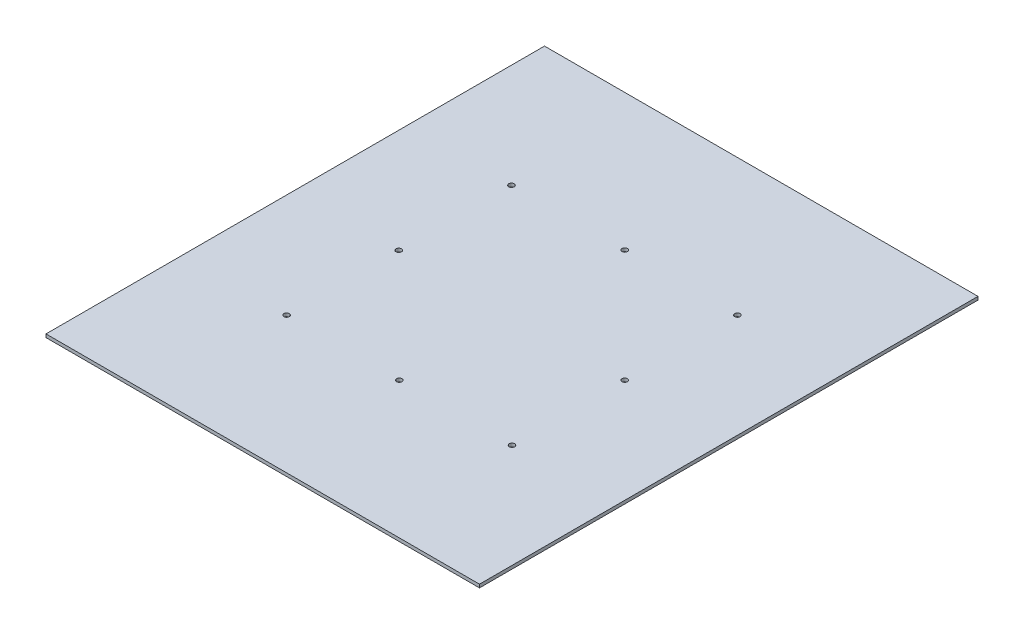
SolidWorks part; units mm, degrees
material "1060 Alloy"
ref_plane "Front Plane" through (0, 0, 0) normal (0, 0, 1) x (1, 0, 0)
ref_plane "Top Plane" through (0, 0, 0) normal (0, 1, 0) x (1, 0, 0)
ref_plane "Right Plane" through (0, 0, 0) normal (1, 0, 0) x (0, 0, -1)
sketch "Sketch1" plane through (0, 0, 0) normal (0, 1, 0) x (1, 0, 0)
  line L1 (0, 0) -> (400, 0)
  line L2 (0, 0) -> (0, 460)
  line L3 (0, 460) -> (400, 460)
  line L4 (400, 0) -> (400, 460)
  circle A0 centre (96, 126) radius 2.5
  circle A1 centre (96, 333.5) radius 2.5
  circle A2 centre (304, 334) radius 2.5
  circle A3 centre (304, 126) radius 2.5
  circle A4 centre (200, 126) radius 2.5
  circle A5 centre (200, 334) radius 2.5
  circle A6 centre (303.9994, 230) radius 2.5
  circle A7 centre (96, 229.5) radius 2.5
  dimension "D3" = 5
  dimension "D4" = 5
  dimension "D5" = 5
  dimension "D6" = 5
  dimension "D11" = 5
  dimension "D16" = 5
  dimension "D17" = 5
  dimension "D19" = 5
  dimension "D1" = 400
  dimension "D2" = 460
  dimension "D7" = 208
  dimension "D8" = 208
  dimension "D9" = 0
  dimension "D10" = 0
  dimension "D12" = 96
  dimension "D13" = 126
  dimension "D14" = 104
  dimension "D15" = 104
  dimension "D18" = 104
  dimension "D20" = 208
  dimension "D21" = 104
  dimension "D22" = 104
  dimension "D23" = 104
extrude "Boss-Extrude1" add sketch "Sketch1" along normal blind 3
